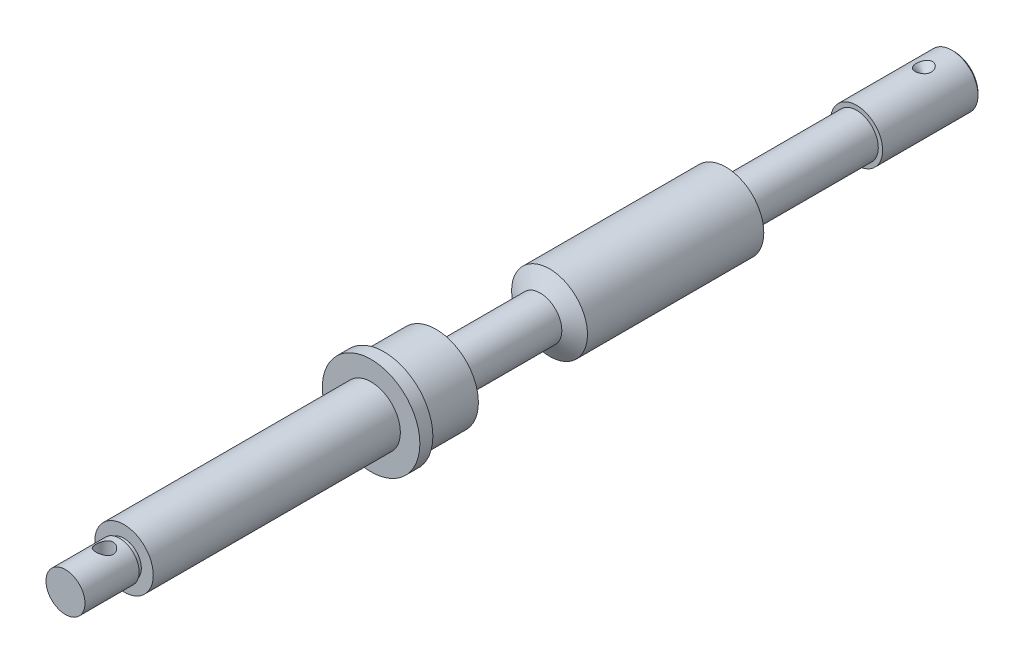
SolidWorks part; units mm, degrees
ref_plane "前视基准面" through (0, 0, 0) normal (0, 0, 1) x (1, 0, 0)
ref_plane "上视基准面" through (0, 0, 0) normal (0, 1, 0) x (1, 0, 0)
ref_plane "右视基准面" through (0, 0, 0) normal (1, 0, 0) x (0, 0, -1)
sketch "草图1" plane through (0, 0, 0) normal (0, 0, 1) x (1, 0, 0)
  circle A0 centre (0, 0) radius 12
  dimension "D1" = 24
extrude "凸台-拉伸1" add sketch "草图1" along normal blind 45
sketch "草图2" plane through (0, 0, 45) normal (0, 0, 1) x (1, 0, 0)
  circle A0 centre (0, 0) radius 10
  dimension "D1" = 20
extrude "凸台-拉伸2" add sketch "草图2" along normal blind 56
sketch "草图3" plane through (0, 0, 101) normal (0, 0, 1) x (1, 0, 0)
  circle A0 centre (0, 0) radius 17.5
  dimension "D1" = 35
extrude "凸台-拉伸3" add sketch "草图3" along normal blind 90
sketch "草图4" plane through (0, 0, 191) normal (0, 0, 1) x (1, 0, 0)
  circle A0 centre (0, 0) radius 10
  dimension "D1" = 20
extrude "凸台-拉伸4" add sketch "草图4" along normal blind 72
sketch "草图5" plane through (0, 0, 263) normal (0, 0, 1) x (1, 0, 0)
  circle A0 centre (0, 0) radius 19.5
  dimension "D1" = 39
extrude "凸台-拉伸5" add sketch "草图5" against normal blind 24
sketch "草图6" plane through (0, 0, 263) normal (0, 0, 1) x (1, 0, 0)
  circle A2 centre (0, 0) radius 18.5
  circle A3 centre (0, 0) radius 18.5
  dimension "D1" = 1
extrude "切除-拉伸1" cut sketch "草图6" against normal blind 2 and the other way through all flip side to cut
sketch "草图7" plane through (0, 0, 263) normal (0, 0, 1) x (1, 0, 0)
  circle A0 centre (0, 0) radius 22.5
  dimension "D1" = 45
extrude "凸台-拉伸6" add sketch "草图7" along normal blind 6
sketch "草图8" plane through (0, 0, 263) normal (0, 0, -1) x (-1, 0, 0)
  circle A0 centre (0, 0) radius 13.5
  dimension "D1" = 27
extrude "凸台-拉伸7" add sketch "草图8" against normal blind 147
sketch "草图10" plane through (0, 0, 410) normal (0, 0, 1) x (1, 0, 0)
  circle A0 centre (0, 0) radius 9
  dimension "D1" = 18
extrude "切除-拉伸2" cut sketch "草图10" against normal blind 27 flip side to cut
sketch "草图11" plane through (0, 0, 383) normal (0, 0, 1) x (1, 0, 0)
  circle A2 centre (0, 0) radius 8
  circle A3 centre (0, 0) radius 8
  dimension "D1" = 1
extrude "切除-拉伸3" cut sketch "草图11" along normal blind 2 flip side to cut
sketch "草图12" plane through (0, 0, 0) normal (1, 0, 0) x (0, 0, -1)
  line L0 (-105.3301, 17.5) -> (-101, 10)
  line L1 (-101, 10) -> (-101, 17.5)
  line L2 (-101, 17.5) -> (-105.3301, 17.5)
  line L3 (-191, 10) -> (-191, 17.5)
  line L4 (-191, 17.5) -> (-191, -17.5) construction
  line L5 (-101, 17.5) -> (-191, 17.5) construction
  line L6 (-191, 17.5) -> (-186.6699, 17.5)
  line L7 (-186.6699, 17.5) -> (-191, 10)
  line L8 (-181.2774, 0) -> (-145.4779, 0) construction
  line L9 (24.75, 0) -> (-24.75, 0) construction
  dimension "D1" = 30
  dimension "D2" = 30
revolve "切除-旋转1" cut sketch "草图12" angle 360 about L8
chamfer "倒角1" distance 1 angle 45 1 edges at (12, 0, 0)
sketch "草图14" plane through (0, 0, 0) normal (1, 0, 0) x (0, 0, -1)
  line L0 (-14, -18.3947) -> (-14, 37.0446) construction
  line L1 (0, 24.75) -> (0, -24.75) construction
  line L2 (-18, 12) -> (-14, 12) construction
  line L3 (-14, 8) -> (-23.2931, 17.2931)
  line L4 (-23.2931, 17.2931) -> (-14, 17.2931)
  line L5 (-14, 17.2931) -> (-14, 8)
  line L6 (-1, 12) -> (-45, 12) construction
  dimension "D1" = 14
  dimension "D2" = 45
  dimension "D3" = 4
revolve "切除-旋转2" cut sketch "草图14" angle 360 about L0
sketch "草图15" plane through (0, 0, 0) normal (0, 1, 0) x (1, 0, 0)
  line L0 (0, -32.7495) -> (0, 32.7495) construction
  line L1 (-9, -410) -> (9, -410) construction
  circle A0 centre (0, -392) radius 4
  dimension "D1" = 8
  dimension "D2" = 18
extrude "切除-拉伸4" cut sketch "草图15" against normal through all both and the other way through all
